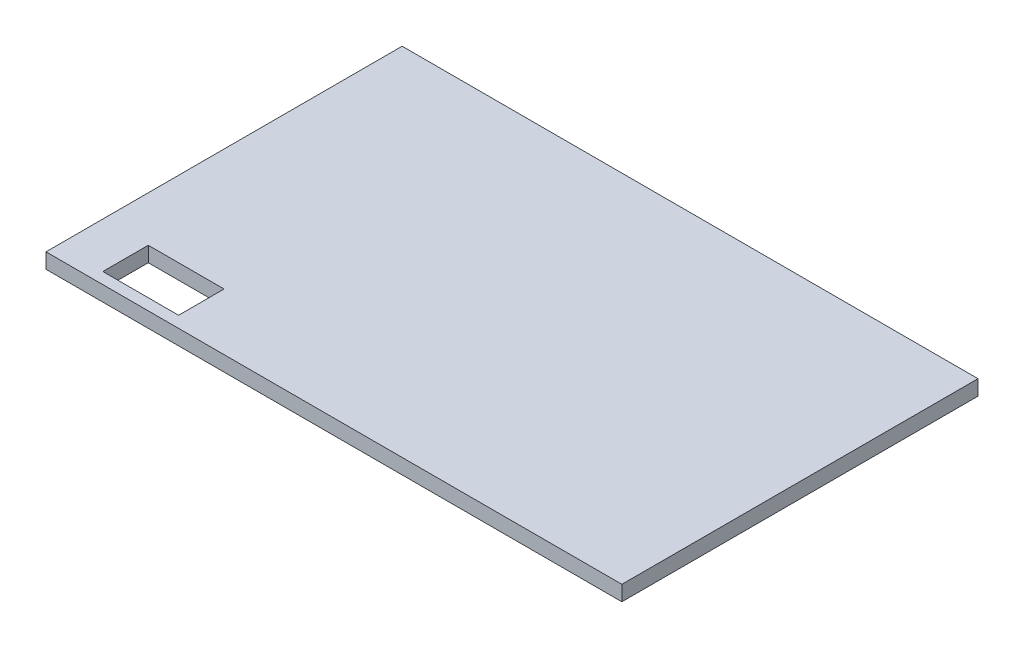
SolidWorks part; units mm, degrees
ref_plane "Front Plane" through (0, 0, 0) normal (0, 0, 1) x (1, 0, 0)
ref_plane "Top Plane" through (0, 0, 0) normal (0, 1, 0) x (1, 0, 0)
ref_plane "Right Plane" through (0, 0, 0) normal (1, 0, 0) x (0, 0, -1)
sketch "Sketch1" plane through (0, 0, 0) normal (0, 1, 0) x (1, 0, 0)
  line L1 (0, 0) -> (40, 0)
  line L2 (0, 0) -> (0, 24)
  line L3 (0, 24) -> (40, 24)
  line L4 (40, 0) -> (40, 24)
  dimension "D1" = 40
  dimension "D2" = 24
extrude "Boss-Extrude1" add sketch "Sketch1" along normal blind 2
sketch "Sketch2" plane through (0, 2, 0) normal (0, 1, 0) x (1, 0, 0)
  line L1 (3, 1) -> (39, 1)
  line L2 (3, 1) -> (3, 23)
  line L3 (3, 23) -> (39, 23)
  line L4 (39, 1) -> (39, 23)
  line L5 (0, 24) -> (40, 24)
  line L6 (0, 24) -> (0, 0)
  line L7 (0, 0) -> (40, 0)
  line L8 (40, 24) -> (40, 0)
  dimension "D1" = 22
  dimension "D2" = 36
  dimension "D3" = 1
  dimension "D4" = 1
extrude "Boss-Extrude3" add sketch "Sketch2" along normal blind 8
sketch "Sketch5" plane through (0, 2, 0) normal (0, 1, 0) x (1, 0, 0)
  line L0 (3, 1) -> (39, 1) construction
  line L1 (4, 1) -> (8, 1)
  line L2 (4, 1) -> (4, 4)
  line L3 (4, 4) -> (8, 4)
  line L4 (8, 1) -> (8, 4)
  line L6 (3, 23) -> (3, 1) construction
  dimension "D1" = 1
  dimension "D2" = 4
  dimension "D3" = 3
extrude "Cut-Extrude1" cut sketch "Sketch5" against normal blind 2
sketch "Sketch6" plane through (40, 0, 0) normal (1, 0, 0) x (0, 0, -1)
  line L1 (0, 10) -> (24, 10)
  line L2 (0, 10) -> (0, 0)
  line L3 (0, 0) -> (24, 0)
  line L4 (24, 10) -> (24, 0)
extrude "Cut-Extrude2" cut sketch "Sketch6" against normal blind 2
sketch "Sketch7" plane through (3, 0, 0) normal (1, 0, 0) x (0, 0, -1)
  line L1 (1, 2) -> (23, 2)
  line L2 (1, 2) -> (1, 10)
  line L3 (1, 10) -> (23, 10)
  line L4 (23, 2) -> (23, 10)
extrude "Cut-Extrude3" cut sketch "Sketch7" against normal blind 2
sketch "Sketch8" plane through (0, 2, 0) normal (0, 1, 0) x (1, 0, 0)
  line L0 (1, 1) -> (4, 1) construction
  line L1 (4, 4) -> (3, 4)
  line L2 (4, 4) -> (4, 1)
  line L3 (4, 1) -> (3, 1)
  line L4 (3, 4) -> (3, 1)
  dimension "D1" = 1
extrude "Cut-Extrude4" cut sketch "Sketch8" against normal blind 2
sketch "Sketch9" plane through (0, 10, 0) normal (0, 1, 0) x (1, 0, 0)
  line L1 (0, 24) -> (38, 24)
  line L2 (0, 24) -> (0, 0)
  line L3 (0, 0) -> (38, 0)
  line L4 (38, 24) -> (38, 0)
extrude "Cut-Extrude5" cut sketch "Sketch9" against normal blind 9
sketch "Sketch10" plane through (0, 0, 0) normal (0, 0, 1) x (1, 0, 0)
  line L1 (0, 0) -> (38, 0)
  line L2 (0, 0) -> (0, 1)
  line L3 (0, 1) -> (38, 1)
  line L4 (38, 0) -> (38, 1)
extrude "Cut-Extrude6" cut sketch "Sketch10" against normal blind 0.25
sketch "Sketch11" plane through (0, 0, -24) normal (0, 0, -1) x (-1, 0, 0)
  line L1 (-38, 0) -> (0, 0)
  line L2 (-38, 0) -> (-38, 1)
  line L3 (-38, 1) -> (0, 1)
  line L4 (0, 0) -> (0, 1)
extrude "Cut-Extrude7" cut sketch "Sketch11" against normal blind 0.25
